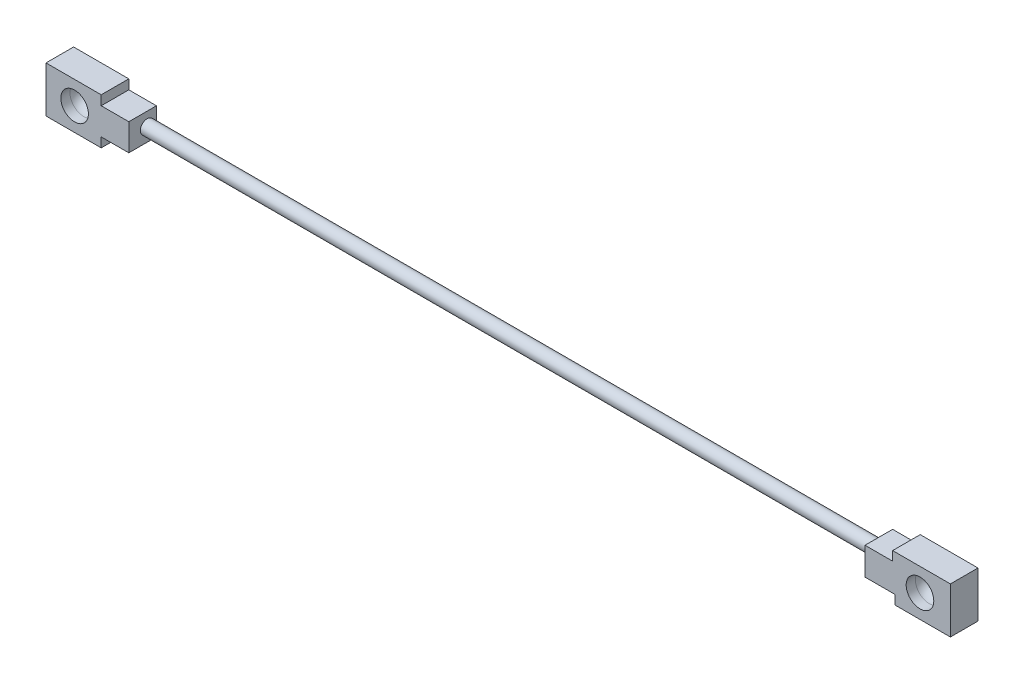
SolidWorks part; units mm, degrees
ref_plane "Front Plane" through (0, 0, 0) normal (0, 0, 1) x (1, 0, 0)
ref_plane "Top Plane" through (0, 0, 0) normal (0, 1, 0) x (1, 0, 0)
ref_plane "Right Plane" through (0, 0, 0) normal (1, 0, 0) x (0, 0, -1)
sketch "Sketch1" plane through (0, 0, 0) normal (0, 0, 1) x (1, 0, 0)
  line L0 (-1000, 0) -> (49000, 0) construction
  line L1 (0, -1000) -> (0, 49000) construction
  line L2 (-3.1068, -2.5) -> (-3.1068, 2.5)
  line L3 (-3.1068, 2.5) -> (2.8932, 2.5)
  line L4 (2.8932, 2.5) -> (2.8932, 1.4644)
  line L5 (2.8932, 1.4644) -> (5.8932, 1.4644)
  line L6 (5.8932, 1.4644) -> (5.8932, -1.4644)
  line L7 (2.8932, -1.4644) -> (5.8932, -1.4644)
  line L8 (2.8932, -2.5) -> (2.8932, -1.4644)
  line L9 (-3.1068, -2.5) -> (2.8932, -2.5)
  point P14 (5.8932, 0)
  point P17 (-3.1068, 0)
  dimension "D1" = 1.0356
  dimension "D2" = 5
  dimension "D3" = 3
  dimension "D4" = 6
  dimension "D5" = 1.4644
extrude "Boss-Extrude1" add sketch "Sketch1" along normal blind 3
sketch "Sketch2" plane through (0, 0, 3) normal (0, 0, 1) x (1, 0, 0)
  circle A0 centre (0, 0) radius 1.5
  dimension "D1" = 3
extrude "Cut-Extrude1" cut sketch "Sketch2" against normal blind 1
sketch "Sketch3" plane through (5.8932, 0, 0) normal (1, 0, 0) x (0, 0, -1)
  line L0 (-1000, 0) -> (49000, 0) construction
  line L1 (-1, -999.456) -> (-1, 49000.544) construction
  line L3 (-2, -998.9897) -> (-2, 49001.0103) construction
  line L5 (-1001.114, 1.5) -> (48998.886, 1.5) construction
  line L7 (0, -1.4644) -> (0, 1.4644) construction
  circle A0 centre (-1, 0) radius 0.75
  dimension "D4" = 1.5
  dimension "D1" = 2
  dimension "D2" = 1
  dimension "D3" = 1.5
extrude "Boss-Extrude2" add sketch "Sketch3" along normal blind 80
sketch "Sketch4" plane through (0, 0, 0) normal (0, 0, 1) x (1, 0, 0)
  line L0 (85.8932, 0.75) -> (85.8932, 1.6069)
  line L1 (85.8932, 1.6069) -> (88.8932, 1.6069)
  line L2 (88.8932, 1.6069) -> (88.8932, 2.6069)
  line L3 (88.8932, 2.6069) -> (95.1709, 2.6069)
  line L4 (95.1709, 2.6069) -> (95.1709, -2.3931)
  line L5 (95.1709, -2.3931) -> (89.1709, -2.3931)
  line L6 (89.1709, -2.3931) -> (89.1709, -1.3931)
  line L7 (89.1709, -1.3931) -> (85.8932, -1.3931)
  line L8 (85.8932, -1.3931) -> (85.8932, -0.75)
  line L9 (-914.1068, 0) -> (49085.8932, 0) construction
  line L10 (85.8932, -0.75) -> (85.8932, 0.75) construction
  line L11 (85.8932, 0.75) -> (85.8932, -0.75)
  line L12 (85.8932, -0.75) -> (85.8987, -0.7423)
  point P18 (85.8932, 0)
  dimension "D1" = 6
  dimension "D2" = 5
  dimension "D3" = 3
  dimension "D4" = 1
  dimension "D5" = 1
extrude "Boss-Extrude3" add sketch "Sketch4" along normal blind 3 contours L11 L0 L1 L2 L3 L4 L5 L6 L7 L8
sketch "Sketch7" plane through (0, 0, 3) normal (0, 0, 1) x (1, 0, 0)
  line L0 (91.8656, -998.8373) -> (91.8656, 49001.1627) construction
  line L1 (88.8932, -998.0063) -> (88.8932, 49001.9937) construction
  line L3 (95.1709, -999.51) -> (95.1709, 49000.49) construction
  line L5 (-914.1068, 0.1069) -> (49085.8932, 0.1069) construction
  line L6 (85.8932, -1.3931) -> (85.8932, 1.6069) construction
  circle A0 centre (91.8656, 0.1069) radius 1.5
  point P11 (85.8932, 0.1069)
  dimension "D1" = 3
extrude "Cut-Extrude2" cut sketch "Sketch7" against normal blind 1
sketch "Sketch8" plane through (0, 0, 2) normal (0, 0, 1) x (1, 0, 0)
  line L0 (91.8656, -999.8931) -> (91.8656, 49000.1069) construction
  line L1 (91.8656, 1.6069) -> (91.8656, -1.3931)
  arc A0 (91.8656, 1.6069) -> (91.8656, -1.3931) centre (91.8656, 0.1069) cw
  circle A1 centre (91.8656, 0.1069) radius 1.5 construction
revolve "Cut-Revolve1" cut sketch "Sketch8" angle 360 about L0
sketch "Sketch9" plane through (0, 0, 2) normal (0, 0, 1) x (1, 0, 0)
  line L0 (0, -1000) -> (0, 49000) construction
  line L1 (0, 1.5) -> (0, -1.5)
  arc A0 (0, 1.5) -> (0, -1.5) centre (0, 0) cw
  circle A1 centre (0, 0) radius 1.5 construction
revolve "Cut-Revolve2" cut sketch "Sketch9" angle 360 about L0
